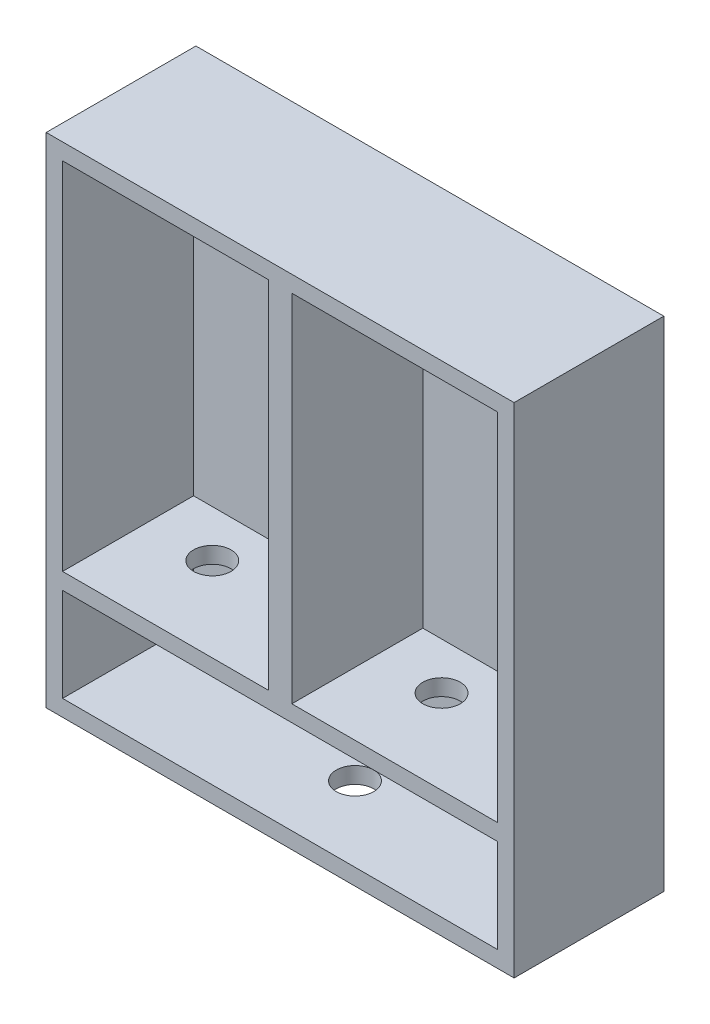
SolidWorks part; units mm, degrees
ref_plane "Front Plane" through (0, 0, 0) normal (0, 0, 1) x (1, 0, 0)
ref_plane "Top Plane" through (0, 0, 0) normal (0, 1, 0) x (1, 0, 0)
ref_plane "Right Plane" through (0, 0, 0) normal (1, 0, 0) x (0, 0, -1)
sketch "Sketch3" plane through (0, 0, 0) normal (0, 0, 1) x (1, 0, 0)
  line L1 (-63.5, 0) -> (0, 0)
  line L2 (-63.5, 0) -> (-63.5, 67.6275)
  line L3 (-63.5, 67.6275) -> (0, 67.6275)
  line L4 (0, 0) -> (0, 67.6275)
  line L5 (-63.5, 0) -> (0, 67.6275) construction
  line L6 (-63.5, 67.6275) -> (0, 0) construction
  point P0 (-31.75, 33.8138)
  point P5 (0, 0)
  point P7 (0, 0)
  point P8 (0, 0)
  dimension "D1" = 67.6275
  dimension "D2" = 63.5
extrude "Boss-Extrude3" add sketch "Sketch3" along normal blind 20.32
sketch "Sketch1" plane through (0, 0, 20.32) normal (0, 0, 1) x (1, 0, 0)
  line L0 (-31.75, 65.405) -> (-31.75, 17.145) construction
  line L1 (-61.2775, 17.145) -> (-2.2225, 17.145)
  line L2 (-61.2775, 17.145) -> (-61.2775, 65.405)
  line L3 (-61.2775, 65.405) -> (-2.2225, 65.405)
  line L4 (-2.2225, 17.145) -> (-2.2225, 65.405)
  line L5 (-61.2775, 17.145) -> (-2.2225, 65.405) construction
  line L6 (-61.2775, 65.405) -> (-2.2225, 17.145) construction
  line L7 (-33.3375, 65.405) -> (-33.3375, 17.145)
  line L8 (-30.1625, 65.405) -> (-30.1625, 17.145)
  line L9 (-63.5, 67.6275) -> (0, 67.6275)
  line L10 (0, 14.9225) -> (0, 67.6275)
  line L11 (-61.2775, 14.9225) -> (-2.2225, 14.9225)
  line L12 (-63.5, 14.9225) -> (-63.5, 67.6275)
  line L13 (-61.2775, 14.9225) -> (-61.2775, 2.2225)
  line L14 (-61.2775, 14.9225) -> (-2.2225, 14.9225)
  line L15 (-63.5, 14.9225) -> (-63.5, 0)
  line L16 (-63.5, 0) -> (0, 0)
  line L17 (0, 14.9225) -> (0, 0)
  line L18 (-61.2775, 2.2225) -> (-2.2225, 2.2225)
  line L19 (-2.2225, 14.9225) -> (-2.2225, 2.2225)
  line L20 (-63.5, 14.9225) -> (0, 14.9225) construction
  line L21 (11.176, 0) -> (-11.176, 0) construction
  point P0 (0, 0)
  point P18 (-86.8385, 0)
  point P25 (0, 0)
  point P29 (-144.699, 67.6275)
  point P30 (-116.7166, 67.6275)
  point P31 (0, 0)
  point P33 (0, 0)
  dimension "D1" = 48.26
  dimension "D5" = 27.94
  dimension "D6" = 12.7
  dimension "D2" = 1.5875
  dimension "D3" = 1.5875
  dimension "D4" = 2.2225
  dimension "D7" = 2.2225
extrude "Cut-Extrude1" cut sketch "Sketch1" against normal blind 17.78 contours L7 L3 L2 L1 | L3 L8 L1 L4 | L19 L11 L13 L18
sketch "Sketch4" plane through (0, 0, 0) normal (0, -1, 0) x (1, 0, 0)
  line L0 (-63.5, 20.32) -> (0, 20.32) construction
  line L1 (-63.5, 20.32) -> (-63.5, 0) construction
  circle A0 centre (-31.75, 10.16) radius 2.54
  point P2 (0, 0)
  point P5 (-31.75, 20.32)
  point P6 (0, 0)
  point P9 (-63.5, 10.16)
  dimension "D1" = 5.08
extrude "Cut-Extrude2" cut sketch "Sketch4" against normal up to surface (2.2225 mm away) up to face at (-31.75, 2.2225, 11.43)
sketch "Sketch5" plane through (0, 14.9225, 0) normal (0, -1, 0) x (-1, 0, 0)
  line L0 (61.2775, -2.54) -> (61.2775, -20.32) construction
  line L1 (2.2225, -2.54) -> (2.2225, -20.32) construction
  line L2 (61.2775, -2.54) -> (2.2225, -2.54) construction
  circle A0 centre (52.3875, -8.89) radius 2.54
  circle A1 centre (21.2725, -8.89) radius 2.54
  point P4 (0, 0)
  dimension "D1" = 8.89
  dimension "D2" = 19.05
  dimension "D3" = 6.35
  dimension "D4" = 5.08
extrude "Cut-Extrude3" cut sketch "Sketch5" against normal up to surface (2.2225 mm away) up to face at (-47.3075, 17.145, 11.43)
sketch "Sketch6" plane through (0, 0, 2.54) normal (0, 0, 1) x (1, 0, 0)
  line L1 (-59.7535, 19.05) -> (-34.8615, 19.05) construction
  line L2 (-59.7535, 19.05) -> (-59.7535, 63.5) construction
  line L3 (-59.7535, 63.5) -> (-34.8615, 63.5) construction
  line L4 (-34.8615, 19.05) -> (-34.8615, 63.5) construction
  line L5 (-59.7535, 19.05) -> (-34.8615, 63.5) construction
  line L6 (-59.7535, 63.5) -> (-34.8615, 19.05) construction
  line L7 (-28.6385, 19.05) -> (-3.7465, 19.05) construction
  line L8 (-28.6385, 19.05) -> (-28.6385, 63.5) construction
  line L9 (-28.6385, 63.5) -> (-3.7465, 63.5) construction
  line L10 (-3.7465, 19.05) -> (-3.7465, 63.5) construction
  line L11 (-28.6385, 19.05) -> (-3.7465, 63.5) construction
  line L12 (-28.6385, 63.5) -> (-3.7465, 19.05) construction
  line L13 (-30.1625, 17.145) -> (-2.2225, 17.145) construction
  line L14 (-30.1625, 17.145) -> (-30.1625, 65.405) construction
  line L15 (-30.1625, 65.405) -> (-2.2225, 65.405) construction
  line L16 (-2.2225, 17.145) -> (-2.2225, 65.405) construction
  line L17 (-30.1625, 17.145) -> (-2.2225, 65.405) construction
  line L18 (-30.1625, 65.405) -> (-2.2225, 17.145) construction
  line L19 (-61.2775, 17.145) -> (-33.3375, 17.145) construction
  line L20 (-61.2775, 17.145) -> (-61.2775, 65.405) construction
  line L21 (-61.2775, 65.405) -> (-33.3375, 65.405) construction
  line L22 (-33.3375, 17.145) -> (-33.3375, 65.405) construction
  line L23 (-61.2775, 17.145) -> (-33.3375, 65.405) construction
  line L24 (-61.2775, 65.405) -> (-33.3375, 17.145) construction
  circle A0 centre (-56.3166, 21.9797) radius 1.397
  circle A1 centre (-23.5825, 21.9797) radius 1.397
  circle A2 centre (-7.5106, 60.1938) radius 1.397
  circle A3 centre (-37.9238, 60.1938) radius 1.397
  point P0 (-47.3075, 41.275)
  point P5 (-16.1925, 41.275)
  point P12 (-16.1925, 41.275)
  point P22 (-47.3075, 41.275)
  dimension "D3" = 2.794
  dimension "D4" = 3.4369
  dimension "D1" = 24.892
  dimension "D2" = 44.45
